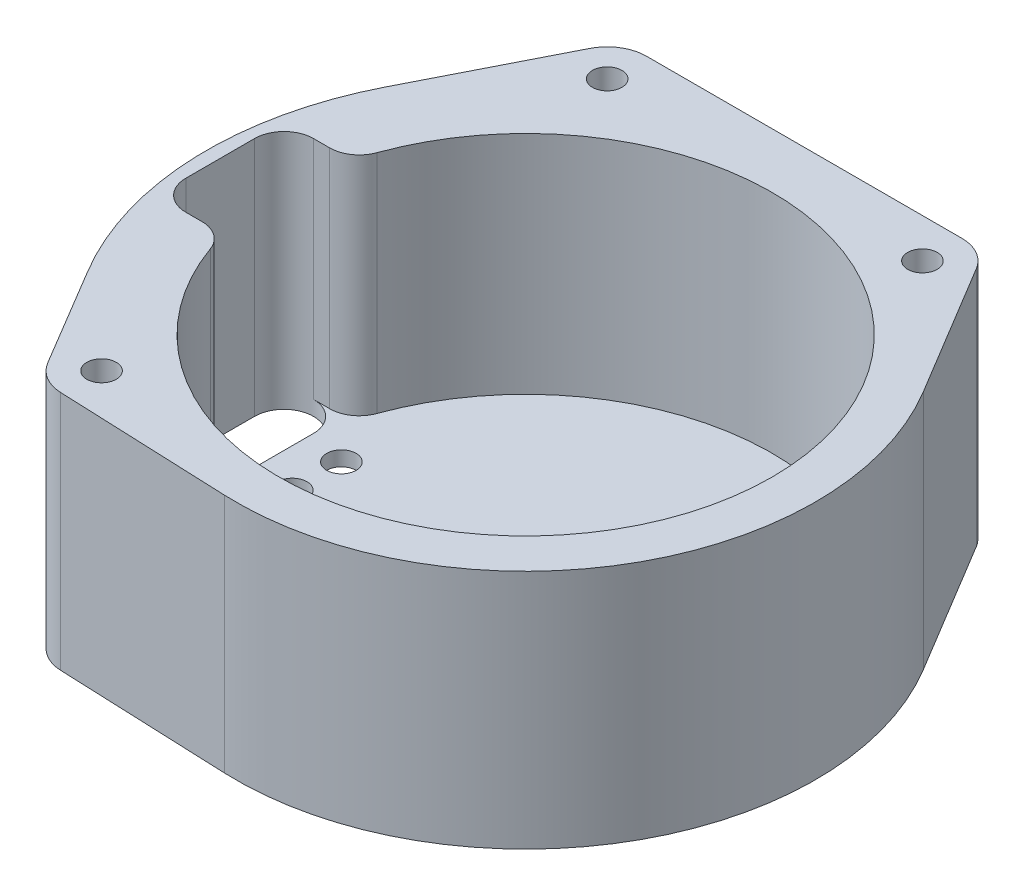
SolidWorks part; units mm, degrees
ref_plane "前视基准面" through (0, 0, 0) normal (0, 0, 1) x (1, 0, 0)
ref_plane "上视基准面" through (0, 0, 0) normal (0, 1, 0) x (1, 0, 0)
ref_plane "右视基准面" through (0, 0, 0) normal (1, 0, 0) x (0, 0, -1)
sketch "Sketch1" plane through (0, 0, 0) normal (0, 1, 0) x (1, 0, 0)
  line L0 (-21.8432, -26.8184) -> (-27.9086, -16.6541)
  line L2 (-28.9848, 14.7014) -> (-21.9757, 28.5204)
  line L3 (-18.5717, -28.7653) -> (-1.2052, -29.4754)
  line L4 (-18.4083, 30.711) -> (13.688, 30.711)
  line L5 (17.1154, 28.7733) -> (25.2769, 15.2094)
  line L6 (-25.1, 0) -> (-31.1, 0) construction
  line L7 (-31.1, -6.5) -> (-31.1, 6.5)
  line L8 (-31.1, 6.5) -> (-24.2438, 6.5)
  line L9 (-31.1, -6.5) -> (-24.2438, -6.5)
  arc A9 (-24.2438, -6.5) -> (-24.2438, 6.5) centre (0, 0) ccw
  circle A10 centre (13.688, 26.711) radius 1.5
  circle A11 centre (-18.4083, 26.711) radius 1.5
  circle A12 centre (-18.4083, -24.7686) radius 1.5
  arc A14 (-18.4083, 30.711) -> (-21.9757, 28.5204) centre (-18.4083, 26.711) ccw
  arc A15 (17.1154, 28.7733) -> (13.688, 30.711) centre (13.688, 26.711) ccw
  arc A16 (-21.8432, -26.8184) -> (-18.5717, -28.7653) centre (-18.4083, -24.7686) ccw
  arc A17 (-1.2052, -29.4754) -> (25.2769, 15.2094) centre (0, 0) ccw
  arc A18 (-28.9848, 14.7014) -> (-27.9086, -16.6541) centre (0, 0) ccw
  dimension "D1" = 32.0963
  dimension "D2" = 51.4797
  dimension "D3" = 24.7686
  dimension "D4" = 18.4083
  dimension "D5" = 26.711
  dimension "D6" = 3
  dimension "D7" = 3
  dimension "D8" = 50.2
  dimension "D13" = 18.4083
  dimension "D9" = 6
  dimension "D10" = 8
  dimension "D11" = 8
  dimension "D12" = 8
  dimension "D14" = 6.5
  dimension "D16" = 65
extrude "Boss-Extrude2" add sketch "Sketch1" along normal blind 23
fillet "Fillet1" radius 3 4 edges at (-31.1, 11.5, -6.5) (-24.2438, 11.5, 6.5) (-24.2438, 11.5, -6.5) (-31.1, 11.5, 6.5)
sketch "Sketch2" plane through (0, 0, 0) normal (0, -1, 0) x (1, 0, 0)
  line L0 (-25.1, 3.5) -> (-25.1, -3.5)
  line L1 (-31.1, 3.5) -> (-31.1, -3.5)
  line L5 (-18.4083, -30.711) -> (13.688, -30.711)
  line L6 (17.1154, -28.7733) -> (25.2769, -15.2094)
  line L7 (-1.2052, 29.4754) -> (-18.5717, 28.7653)
  line L8 (-21.8432, 26.8184) -> (-27.9086, 16.6541)
  line L9 (-28.9848, -14.7014) -> (-21.9757, -28.5204)
  line L10 (-18.4083, -30.711) -> (13.688, -30.711)
  line L11 (17.1154, -28.7733) -> (25.2769, -15.2094)
  line L12 (-1.2052, 29.4754) -> (-18.5717, 28.7653)
  line L13 (-21.8432, 26.8184) -> (-27.9086, 16.6541)
  line L14 (-28.9848, -14.7014) -> (-21.9757, -28.5204)
  circle A0 centre (0, 0) radius 6
  circle A1 centre (13.688, -26.711) radius 1.5
  circle A2 centre (-18.4083, -26.711) radius 1.5
  circle A3 centre (-18.4083, 24.7686) radius 1.5
  arc A4 (-31.1, -3.5) -> (-25.1, -3.5) centre (-28.1, -3.5) ccw
  arc A5 (-21.9757, -28.5204) -> (-18.4083, -30.711) centre (-18.4083, -26.711) ccw
  arc A6 (13.688, -30.711) -> (17.1154, -28.7733) centre (13.688, -26.711) ccw
  arc A7 (25.2769, -15.2094) -> (-1.2052, 29.4754) centre (0, 0) ccw
  arc A8 (-18.5717, 28.7653) -> (-21.8432, 26.8184) centre (-18.4083, 24.7686) ccw
  arc A9 (-27.9086, 16.6541) -> (-28.9848, -14.7014) centre (0, 0) ccw
  arc A10 (-21.9757, -28.5204) -> (-18.4083, -30.711) centre (-18.4083, -26.711) ccw
  arc A11 (13.688, -30.711) -> (17.1154, -28.7733) centre (13.688, -26.711) ccw
  arc A12 (25.2769, -15.2094) -> (-1.2052, 29.4754) centre (0, 0) ccw
  arc A13 (-18.5717, 28.7653) -> (-21.8432, 26.8184) centre (-18.4083, 24.7686) ccw
  arc A14 (-27.9086, 16.6541) -> (-28.9848, -14.7014) centre (0, 0) ccw
  arc A15 (-25.1, 3.5) -> (-31.1, 3.5) centre (-28.1, 3.5) ccw
  dimension "D2" = 12
  dimension "D1" = 0
extrude "Boss-Extrude3" add sketch "Sketch2" along normal blind 1.5
sketch "Sketch3" plane through (0, -1.5, 0) normal (0, -1, 0) x (1, 0, 0)
sketch "Sketch4" plane through (0, -1.5, 0) normal (0, -1, 0) x (1, 0, 0)
  circle A0 centre (-21.1709, 2.5873) radius 1.5
  circle A1 centre (-21.1709, -2.4127) radius 1.5
extrude "Cut-Extrude1" cut sketch "Sketch4" against normal blind 2
